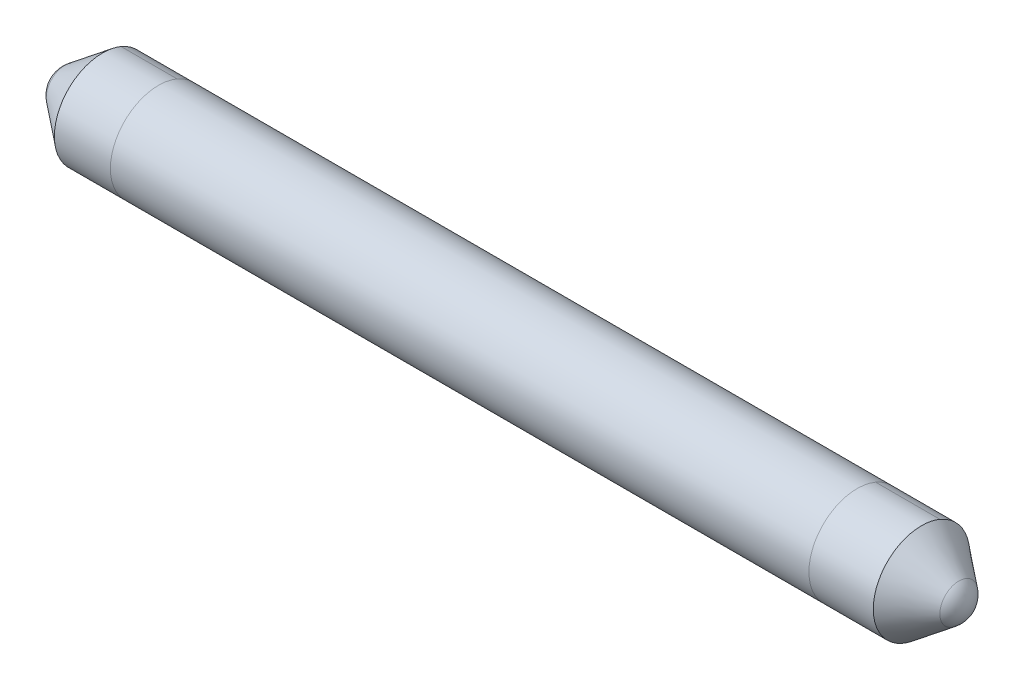
SolidWorks part; units mm, degrees
ref_plane "Plane1" through (0, 0, 0) normal (0, 0, 1) x (1, 0, 0)
ref_plane "Plane2" through (0, 0, 0) normal (0, 1, 0) x (1, 0, 0)
ref_plane "Plane3" through (0, 0, 0) normal (1, 0, 0) x (0, 0, -1)
other "Configuration Table"
sketch "Sketch1" plane through (0, 0, 0) normal (0, 0, 1) x (1, 0, 0)
  line L0 (0, -101.644) -> (-189.3727, -101.644)
  line L2 (-100, -81.644) -> (0, -81.644)
  line L3 (0, -81.644) -> (0, -101.644)
  line L4 (-160, -81.644) -> (-100, -81.644)
  line L5 (-170, -81.644) -> (-160, -81.644)
  line L7 (-170, -81.644) -> (-185.5252, -93.7607)
  line L8 (0, -101.644) -> (-189.3727, -101.644) construction
  arc A0 (-189.3727, -101.644) -> (-185.5252, -93.7607) centre (-179.3727, -101.644) cw
  dimension "D1" = 10
revolve "Base-Revolve" add sketch "Sketch1" angle 360 about L8
mirror "Mirror1" about plane through (0, 0, 0) normal (1, 0, 0) of "Base-Revolve"
sketch "Sketch2" plane through (0, 0, 0) normal (0, 0, 1) x (1, 0, 0)
  line L2 (-146.7494, -181.4119) -> (-146.7494, -61.9651)
split line "Split Line6"
sketch "Sketch15" plane through (0, 0, 0) normal (0, 0, 1) x (1, 0, 0)
  line L1 (143.2847, -65.1497) -> (143.2847, -144.6165)
split line "Split Line26"
split line "Split Line29"
sketch "Sketch2" plane through (0, -79.6373, 36.2633) normal (0, 0.9101, -0.4144) x (-1, 0, 0)
  line L0 (-233.0538, -41.4662) -> (212.4902, -41.4662)
